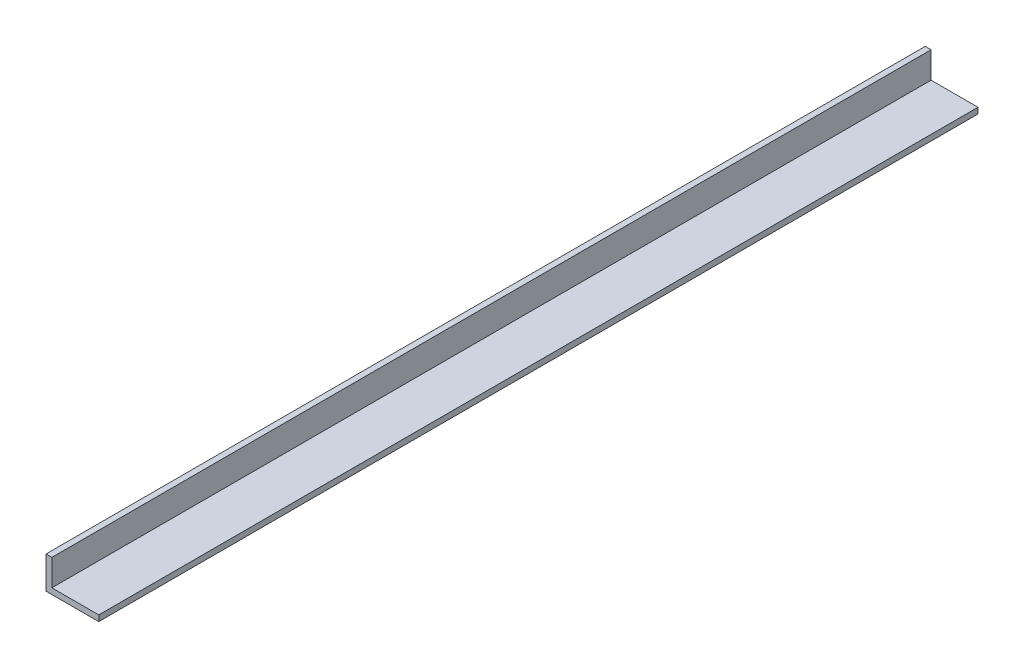
SolidWorks part; units mm, degrees
ref_plane "Front Plane" through (0, 0, 0) normal (0, 0, 1) x (1, 0, 0)
ref_plane "Top Plane" through (0, 0, 0) normal (0, 1, 0) x (1, 0, 0)
ref_plane "Right Plane" through (0, 0, 0) normal (1, 0, 0) x (0, 0, -1)
sketch "Sketch1" plane through (0, 0, 0) normal (0, 0, 1) x (1, 0, 0)
  line L0 (0, 17.4625) -> (0, 0)
  line L1 (0, 0) -> (28.575, 0)
  line L2 (28.575, 0) -> (28.575, 3.175)
  line L3 (28.575, 3.175) -> (3.175, 3.175)
  line L4 (3.175, 3.175) -> (3.175, 17.4625)
  line L5 (3.175, 17.4625) -> (0, 17.4625)
  dimension "D1" = 3.175
  dimension "D2" = 3.175
  dimension "D3" = 25.4
  dimension "D4" = 14.2875
extrude "Boss-Extrude1" add sketch "Sketch1" along normal blind 476.25
